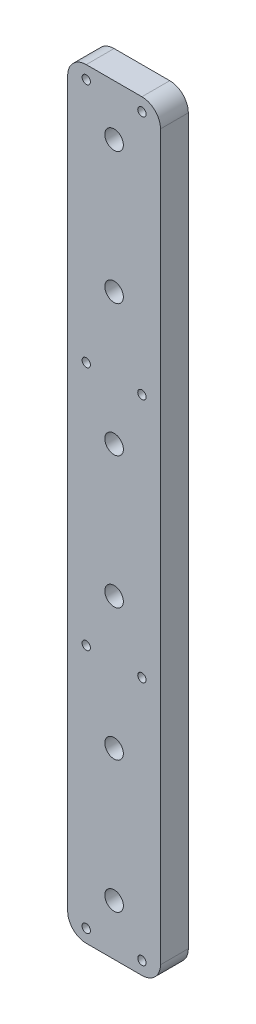
SolidWorks part; units mm, degrees
ref_plane "Front" through (0, 0, 0) normal (0, 0, 1) x (1, 0, 0)
ref_plane "Top" through (0, 0, 0) normal (0, 1, 0) x (1, 0, 0)
ref_plane "Right" through (0, 0, 0) normal (1, 0, 0) x (0, 0, -1)
sketch "Esquisse1" plane through (0, 0, 0) normal (0, 0, 1) x (1, 0, 0)
  line L1 (0, 0) -> (50, 0)
  line L2 (0, 0) -> (0, 410)
  line L3 (0, 410) -> (50, 410)
  line L4 (50, 0) -> (50, 410)
  dimension "D1" = 50
  dimension "D2" = 410
extrude "Boss.-Extru.1" add sketch "Esquisse1" along normal blind 15
sketch "Esquisse2" plane through (0, 0, 15) normal (0, 0, 1) x (1, 0, 0)
  line L0 (50, 205) -> (0, 205) construction
  line L1 (50, 0) -> (50, 410) construction
  line L2 (0, 410) -> (0, 0) construction
  line L3 (25, 240.5) -> (25, 205) construction
  line L4 (25, 240.5) -> (25, 311.5) construction
  line L5 (25, 311.5) -> (25, 382.5) construction
  line L6 (25, 98.5) -> (25, 27.5) construction
  line L7 (25, 169.5) -> (25, 98.5) construction
  line L8 (40, 205) -> (40, 271) construction
  line L9 (40, 271) -> (40, 403) construction
  line L10 (40, 139) -> (40, 7) construction
  line L11 (10, 139) -> (10, 7) construction
  line L12 (10, 271) -> (10, 403) construction
  line L13 (10, 205) -> (10, 271) construction
  circle A0 centre (25, 240.5) radius 5
  circle A1 centre (25, 311.5) radius 5
  circle A2 centre (25, 382.5) radius 5
  circle A3 centre (25, 27.5) radius 5
  circle A4 centre (25, 98.5) radius 5
  circle A5 centre (25, 169.5) radius 5
  circle A6 centre (40, 271) radius 2.25
  circle A7 centre (40, 403) radius 2.25
  circle A8 centre (40, 7) radius 2.25
  circle A9 centre (40, 139) radius 2.25
  circle A10 centre (10, 139) radius 2.25
  circle A11 centre (10, 7) radius 2.25
  circle A12 centre (10, 403) radius 2.25
  circle A13 centre (10, 271) radius 2.25
  dimension "D1" = 10
  dimension "D2" = 71
  dimension "D3" = 71
  dimension "D4" = 71
  dimension "D7" = 4.5
  dimension "D5" = 66
  dimension "D6" = 15
  dimension "D8" = 132
extrude "Enlèv. mat.-Extru.1" cut sketch "Esquisse2" against normal through all both and the other way through all
fillet "Congé1" radius 10 4 edges at (50, 0, 7.5) (0, 0, 7.5) (50, 410, 7.5) (0, 410, 7.5)
